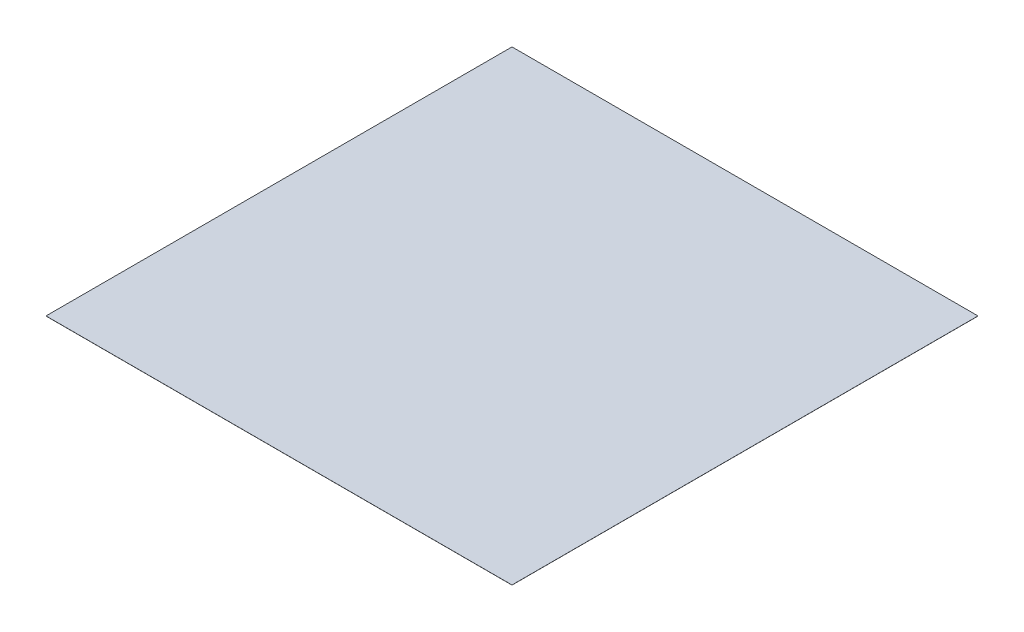
SolidWorks part; units mm, degrees
ref_plane "前视基准面" through (0, 0, 0) normal (0, 0, 1) x (1, 0, 0)
ref_plane "上视基准面" through (0, 0, 0) normal (0, 1, 0) x (1, 0, 0)
ref_plane "右视基准面" through (0, 0, 0) normal (1, 0, 0) x (0, 0, -1)
sketch "草图1" plane through (0, 0, 0) normal (0, 1, 0) x (1, 0, 0)
  line L5 (-200, -200) -> (200, -200)
  line L6 (-200, -200) -> (-200, 200)
  line L7 (-200, 200) -> (200, 200)
  line L8 (200, -200) -> (200, 200)
  line L9 (-200, -200) -> (200, 200) construction
  line L10 (-200, 200) -> (200, -200) construction
  point P0 (0, 0)
  dimension "D1" = 400
extrude "凸台-拉伸1" add sketch "草图1" along normal mid plane 0.1
